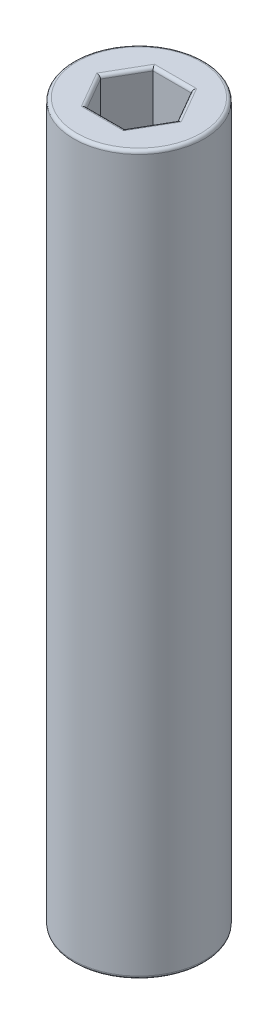
SolidWorks part; units mm, degrees
ref_plane "Front Plane" through (0, 0, 0) normal (0, 0, 1) x (1, 0, 0)
ref_plane "Top Plane" through (0, 0, 0) normal (0, 1, 0) x (1, 0, 0)
ref_plane "Right Plane" through (0, 0, 0) normal (1, 0, 0) x (0, 0, -1)
sketch "Sketch1" plane through (0, 0, 0) normal (0, 1, 0) x (1, 0, 0)
  line L1 (7.479, 0) -> (3.7395, 6.477)
  line L2 (3.7395, 6.477) -> (-3.7395, 6.477)
  line L3 (-3.7395, 6.477) -> (-7.479, 0)
  line L4 (-7.479, 0) -> (-3.7395, -6.477)
  line L5 (-3.7395, -6.477) -> (3.7395, -6.477)
  line L6 (3.7395, -6.477) -> (7.479, 0)
  circle A0 centre (0, 0) radius 6.477 construction
  circle A1 centre (0, 0) radius 12.7
  point P10 (0, 0)
  dimension "D2" = 25.4
  dimension "D1" = 12.954
extrude "Boss-Extrude1" add sketch "Sketch1" along normal blind 139.7
fillet "Fillet1" radius 0.635 14 edges at (0, 139.7, -6.477) (-5.6092, 139.7, -3.2385) (-5.6092, 139.7, 3.2385) (0, 139.7, 6.477) (5.6092, 139.7, 3.2385) (5.6092, 139.7, -3.2385) (0, 139.7, 12.7) (0, 0, 6.477) (-5.6092, 0, 3.2385) (-5.6092, 0, -3.2385) (0, 0, -6.477) (5.6092, 0, -3.2385) (5.6092, 0, 3.2385) (0, 0, 12.7)
